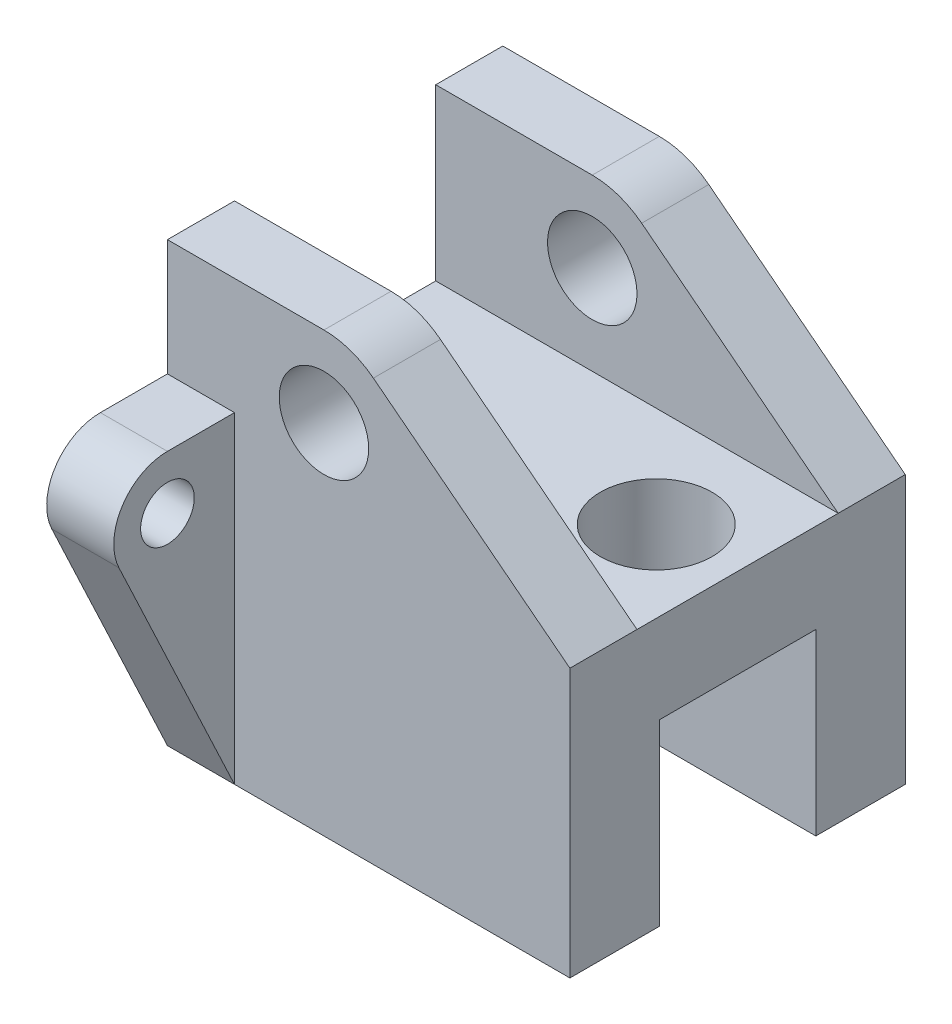
SolidWorks part; units mm, degrees
ref_plane "Front Plane" through (0, 0, 0) normal (0, 0, 1) x (1, 0, 0)
ref_plane "Top Plane" through (0, 0, 0) normal (0, 1, 0) x (1, 0, 0)
ref_plane "Right Plane" through (0, 0, 0) normal (1, 0, 0) x (0, 0, -1)
sketch "Sketch1" plane through (0, 0, 0) normal (1, 0, 0) x (0, 0, -1)
  line L0 (-25.7937, 0) -> (-25.7937, 60)
  line L1 (-25.7937, 60) -> (49.2063, 60)
  line L2 (49.2063, 60) -> (49.2063, 0)
  line L3 (49.2063, 0) -> (29.2063, 0)
  line L4 (29.2063, 0) -> (29.2063, 40)
  line L5 (29.2063, 40) -> (-5.7937, 40)
  line L6 (-5.7937, 40) -> (-5.7937, 0)
  line L7 (-5.7937, 0) -> (-25.7937, 0)
  dimension "D1" = 20
  dimension "D2" = 20
  dimension "D3" = 35
  dimension "D4" = 40
  dimension "D5" = 60
extrude "Boss-Extrude1" add sketch "Sketch1" against normal blind 90
sketch "Sketch2" plane through (0, 0, 25.7937) normal (0, 0, 1) x (1, 0, 0)
  line L0 (0, 60) -> (-43.9439, 94.2043)
  line L1 (-55, 98) -> (-90, 98)
  line L2 (-90, 98) -> (-90, 60)
  line L3 (-90, 60) -> (0, 60)
  arc A0 (-43.9439, 94.2043) -> (-55, 98) centre (-55, 80) ccw
  circle A1 centre (-55, 80) radius 10
  dimension "D1" = 18
  dimension "D2" = 20
  dimension "D3" = 35
extrude "Boss-Extrude2" add sketch "Sketch2" against normal blind 15
sketch "Sketch3" plane through (0, 0, -49.2063) normal (0, 0, -1) x (-1, 0, 0)
  line L0 (0, 60) -> (90, 60)
  line L1 (90, 60) -> (90, 98)
  line L2 (90, 98) -> (55, 98)
  line L3 (43.9439, 94.2043) -> (0, 60)
  arc A0 (55, 98) -> (43.9439, 94.2043) centre (55, 80) ccw
  circle A1 centre (55, 80) radius 10
  dimension "D1" = 18
  dimension "D2" = 35
extrude "Boss-Extrude3" add sketch "Sketch3" against normal blind 15
sketch "Sketch5" plane through (-90, 0, 0) normal (-1, 0, 0) x (0, 0, 1)
  line L16 (25.7937, 0) -> (25.7937, 72)
  line L17 (25.7937, 98) -> (25.7937, 0) construction
  line L18 (25.7937, 72) -> (40.7937, 72)
  line L21 (25.7937, 0) -> (51.6494, 54.8861)
  arc A2 (40.7937, 72) -> (51.6494, 54.8861) centre (40.7937, 60) cw
  circle A3 centre (40.7937, 60) radius 6
  dimension "D1" = 12
  dimension "D3" = 60
  dimension "D2" = 15
extrude "Boss-Extrude4" add sketch "Sketch5" against normal blind 15
sketch "Sketch6" plane through (-90, 0, 0) normal (-1, 0, 0) x (0, 0, 1)
  line L0 (-49.2063, 0) -> (-75.0621, 54.8861)
  line L1 (-64.2063, 72) -> (-49.2063, 72)
  line L2 (-49.2063, 0) -> (-49.2063, 98) construction
  line L3 (-49.2063, 72) -> (-49.2063, 0)
  arc A0 (-64.2063, 72) -> (-75.0621, 54.8861) centre (-64.2063, 60) ccw
  circle A1 centre (-64.2063, 60) radius 6
  dimension "D1" = 12
  dimension "D2" = 60
  dimension "D3" = 15
extrude "Boss-Extrude5" add sketch "Sketch6" against normal blind 15
sketch "Sketch7" plane through (0, 60, 0) normal (0, 1, 0) x (1, 0, 0)
  line L0 (-43.9439, 34.2063) -> (0, 34.2063) construction
  circle A0 centre (-18.195, 11.7063) radius 12.5
  dimension "D1" = 22.5
extrude "Cut-Extrude1" cut sketch "Sketch7" against normal through all
